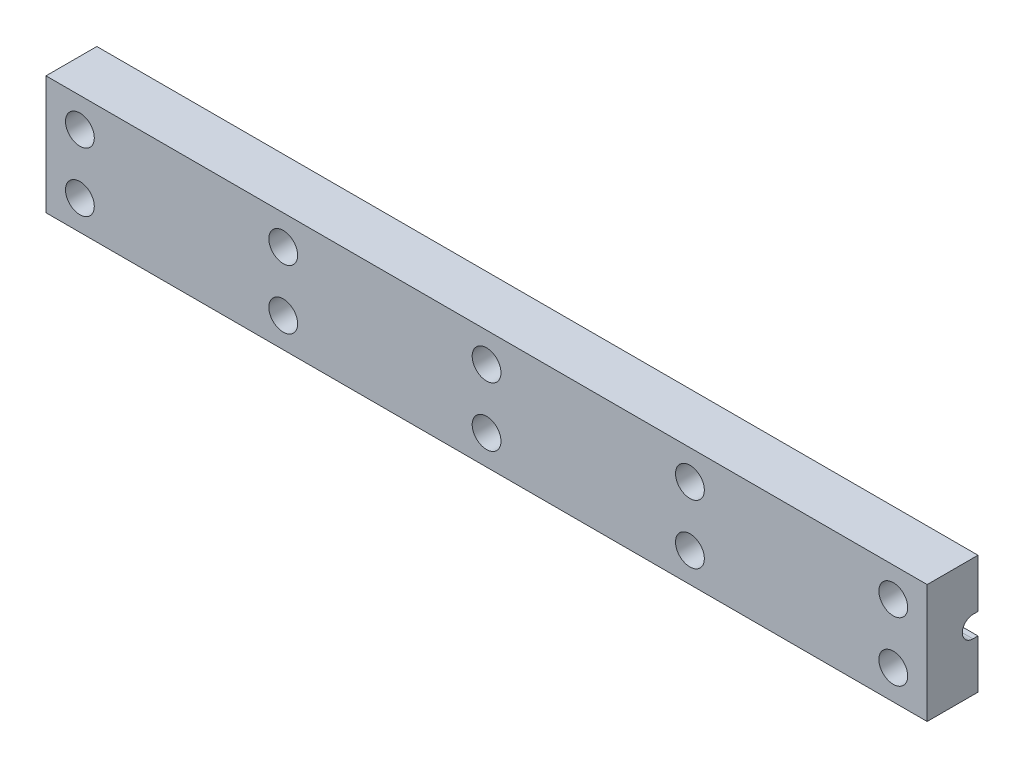
SolidWorks part; units mm, degrees
ref_plane "Front Plane" through (0, 0, 0) normal (0, 0, 1) x (1, 0, 0)
ref_plane "Top Plane" through (0, 0, 0) normal (0, 1, 0) x (1, 0, 0)
ref_plane "Right Plane" through (0, 0, 0) normal (1, 0, 0) x (0, 0, -1)
ref_plane "Plane1" through (190.6451, 0, 0) normal (1, 0, 0) x (0, 0, -1)
sketch "Sketch1" plane through (190.6451, 0, 0) normal (1, 0, 0) x (0, 0, -1)
  line L0 (-246.9709, 208.1635) -> (-246.9709, 205.1635) construction
  line L1 (-240.9709, 205.1635) -> (-240.9709, 208.1635) construction
  line L2 (-240.9709, 208.1635) -> (-246.9709, 208.1635) construction
  line L3 (-240.9709, 199.9135) -> (-241.5709, 199.9135) construction
  line L4 (-241.5709, 202.4135) -> (-240.9709, 202.4135) construction
  line L5 (-240.9709, 202.4135) -> (-240.9709, 205.1635) construction
  line L6 (-246.9709, 205.1635) -> (-246.9709, 197.1635) construction
  line L7 (-240.9709, 197.1635) -> (-240.9709, 199.9135) construction
  line L8 (-246.9709, 197.1635) -> (-246.9709, 194.1635) construction
  line L9 (-246.9709, 194.1635) -> (-240.9709, 194.1635) construction
  line L10 (-240.9709, 194.1635) -> (-240.9709, 197.1635) construction
  line L11 (-246.9709, 208.1635) -> (-246.9709, 205.1635)
  line L12 (-240.9709, 205.1635) -> (-240.9709, 208.1635)
  line L13 (-240.9709, 208.1635) -> (-246.9709, 208.1635)
  line L14 (-240.9709, 199.9135) -> (-241.5709, 199.9135)
  line L15 (-241.5709, 202.4135) -> (-240.9709, 202.4135)
  line L16 (-240.9709, 202.4135) -> (-240.9709, 205.1635)
  line L17 (-246.9709, 205.1635) -> (-246.9709, 197.1635)
  line L18 (-240.9709, 197.1635) -> (-240.9709, 199.9135)
  line L19 (-246.9709, 197.1635) -> (-246.9709, 194.1635)
  line L20 (-246.9709, 194.1635) -> (-240.9709, 194.1635)
  line L21 (-240.9709, 194.1635) -> (-240.9709, 197.1635)
  arc A0 (-241.5709, 202.4135) -> (-241.5709, 199.9135) centre (-241.5709, 201.1635) ccw construction
  arc A1 (-241.5709, 202.4135) -> (-241.5709, 199.9135) centre (-241.5709, 201.1635) ccw
extrude "Boss-Extrude1" add sketch "Sketch1" along normal blind 60 and the other way blind 20
sketch "Sketch2" plane through (0, 0, 246.9709) normal (0, 0, 1) x (1, 0, 0)
  line L0 (170.6451, 201.1635) -> (250.6451, 201.1635) construction
  line L1 (170.6451, 208.1635) -> (170.6451, 194.1635) construction
  line L2 (170.6451, 201.1635) -> (170.6451, 208.1635) construction
  line L3 (170.6451, 204.6635) -> (250.6451, 204.6635) construction
  line L4 (170.6451, 194.1635) -> (250.6451, 194.1635)
  line L5 (250.6451, 194.1635) -> (250.6451, 208.1635)
  line L6 (250.6451, 208.1635) -> (170.6451, 208.1635)
  line L7 (170.6451, 208.1635) -> (170.6451, 194.1635)
  line L8 (170.6451, 194.1635) -> (250.6451, 194.1635) construction
  line L9 (250.6451, 194.1635) -> (250.6451, 208.1635) construction
  line L10 (250.6451, 208.1635) -> (170.6451, 208.1635) construction
  line L12 (250.6451, 201.1635) -> (250.6451, 194.1635)
  line L13 (250.6451, 197.6635) -> (170.6451, 197.6635) construction
  line L15 (246.6451, 197.6635) -> (250.6451, 197.6635)
  line L16 (174.6451, 197.6635) -> (170.6451, 197.6635)
  line L17 (246.6451, 197.6635) -> (222.6451, 197.6635) construction
  line L18 (174.6451, 197.6635) -> (198.6451, 197.6635)
  line L20 (246.6451, 204.6635) -> (222.6451, 204.6635) construction
  circle A0 centre (246.6451, 197.6635) radius 1.7
  circle A2 centre (174.6451, 197.6635) radius 1.7
  circle A3 centre (198.6451, 197.6635) radius 1.7
  circle A4 centre (222.6451, 197.6635) radius 1.7
  circle A5 centre (174.6451, 204.6635) radius 1.7
  circle A6 centre (198.6451, 204.6635) radius 1.7
  circle A7 centre (222.6451, 204.6635) radius 1.7
  circle A8 centre (246.6451, 204.6635) radius 1.7
  dimension "D2" = 3.4
  dimension "D3" = 4
  dimension "D4" = 4
  dimension "D5" = 24
  dimension "D6" = 24
  dimension "D1" = 0
extrude "Cut-Extrude1" cut sketch "Sketch2" against normal blind 10
sketch "Sketch3" plane through (170.6451, 0, 0) normal (-1, 0, 0) x (0, 0, 1)
  line L7 (246.9709, 208.1635) -> (240.9709, 208.1635)
  line L8 (240.9709, 208.1635) -> (240.9709, 202.4135)
  line L9 (240.9709, 202.4135) -> (241.5709, 202.4135)
  line L10 (241.5709, 199.9135) -> (240.9709, 199.9135)
  line L11 (240.9709, 199.9135) -> (240.9709, 194.1635)
  line L12 (240.9709, 194.1635) -> (246.9709, 194.1635)
  line L13 (246.9709, 194.1635) -> (246.9709, 208.1635)
  line L14 (246.9709, 208.1635) -> (240.9709, 208.1635)
  line L15 (240.9709, 208.1635) -> (240.9709, 202.4135)
  line L16 (240.9709, 202.4135) -> (241.5709, 202.4135)
  line L17 (241.5709, 199.9135) -> (240.9709, 199.9135)
  line L18 (240.9709, 199.9135) -> (240.9709, 194.1635)
  line L19 (240.9709, 194.1635) -> (246.9709, 194.1635)
  line L20 (246.9709, 194.1635) -> (246.9709, 208.1635)
  arc A1 (241.5709, 199.9135) -> (241.5709, 202.4135) centre (241.5709, 201.1635) ccw
  arc A2 (241.5709, 199.9135) -> (241.5709, 202.4135) centre (241.5709, 201.1635) ccw
  dimension "D1" = 0
extrude "Boss-Extrude2" add sketch "Sketch3" along normal blind 24
sketch "Sketch4" plane through (0, 0, 246.9709) normal (0, 0, 1) x (1, 0, 0)
  line L0 (174.6451, 197.6635) -> (150.6451, 197.6635)
  line L1 (174.6451, 204.6635) -> (150.6451, 204.6635)
  circle A0 centre (150.6451, 197.6635) radius 1.7
  circle A1 centre (198.6451, 204.6635) radius 1.7
  circle A2 centre (198.6451, 204.6635) radius 1.7
  circle A3 centre (174.6451, 197.6635) radius 1.7
  circle A4 centre (174.6451, 197.6635) radius 1.7
  circle A5 centre (222.6451, 197.6635) radius 1.7
  circle A6 centre (222.6451, 197.6635) radius 1.7
  circle A7 centre (246.6451, 204.6635) radius 1.7
  circle A8 centre (246.6451, 204.6635) radius 1.7
  circle A9 centre (246.6451, 197.6635) radius 1.7
  circle A10 centre (246.6451, 197.6635) radius 1.7
  circle A11 centre (174.6451, 204.6635) radius 1.7
  circle A12 centre (174.6451, 204.6635) radius 1.7
  circle A13 centre (198.6451, 197.6635) radius 1.7
  circle A14 centre (198.6451, 197.6635) radius 1.7
  circle A15 centre (222.6451, 204.6635) radius 1.7
  circle A16 centre (222.6451, 204.6635) radius 1.7
  circle A17 centre (150.6451, 204.6635) radius 1.7
  dimension "D9" = 24
  dimension "D1" = 0
  dimension "D2" = 0
  dimension "D3" = 0
  dimension "D4" = 0
  dimension "D5" = 0
  dimension "D6" = 0
  dimension "D7" = 0
  dimension "D8" = 0
extrude "Cut-Extrude2" cut sketch "Sketch4" against normal blind 24
equation "\"D6@Sketch2\"=\"D5@Sketch2\""
